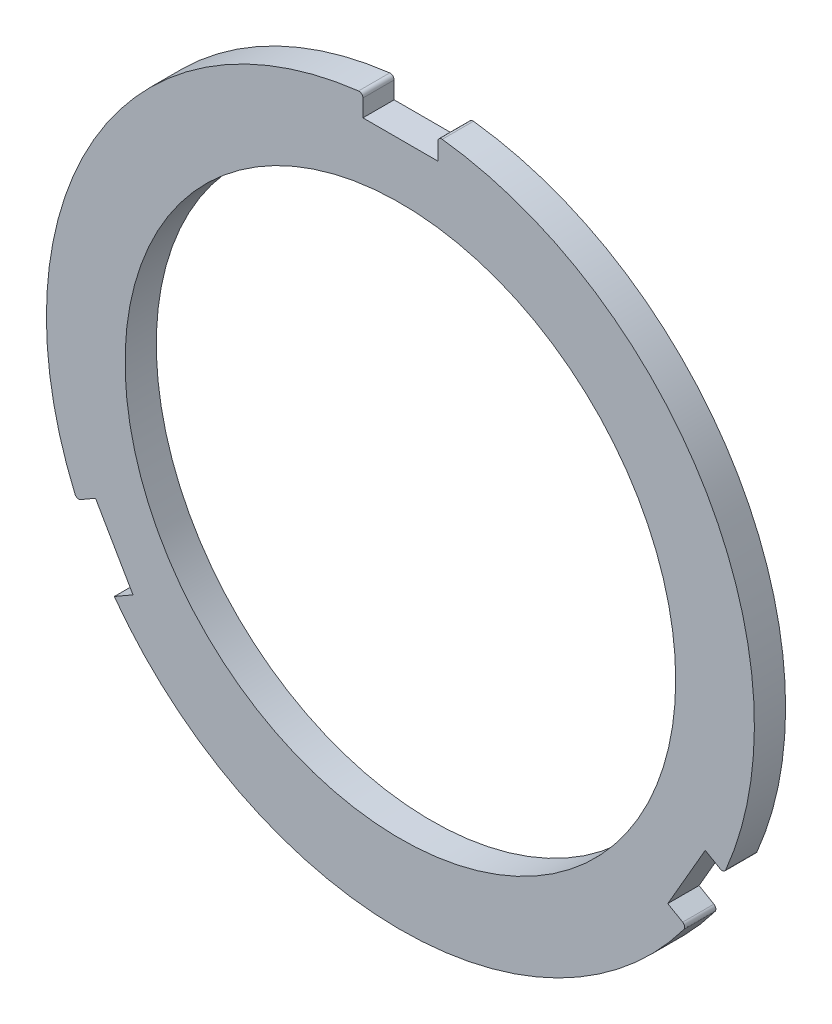
SolidWorks part; units mm, degrees
ref_plane "前基準面" through (0, 0, 0) normal (0, 0, 1) x (1, 0, 0)
ref_plane "上基準面" through (0, 0, 0) normal (0, 1, 0) x (1, 0, 0)
ref_plane "右基準面" through (0, 0, 0) normal (1, 0, 0) x (0, 0, -1)
sketch "Sketch1" plane through (0, 0, 0) normal (0, 0, 1) x (1, 0, 0)
  line L0 (0, 0) -> (0, 33.8653) construction
  line L1 (0, 0) -> (29.3282, -16.9326) construction
  line L2 (0, 0) -> (-29.3282, -16.9326) construction
  line L3 (0, 21) -> (2.3813, 21)
  line L4 (2.3813, 21) -> (2.3813, 22.3736)
  line L5 (20.5668, -9.1246) -> (19.3772, -8.4378)
  line L6 (-2.3812, 22.3736) -> (-2.3813, 21)
  line L7 (-2.3813, 21) -> (0, 21)
  line L8 (19.3772, -8.4378) -> (18.1865, -10.5)
  line L9 (18.1865, -10.5) -> (16.9959, -12.5622)
  line L10 (16.9959, -12.5622) -> (18.1855, -13.249)
  line L11 (-18.1855, -13.249) -> (-16.9959, -12.5622)
  line L12 (-16.9959, -12.5622) -> (-18.1865, -10.5)
  line L13 (-18.1865, -10.5) -> (-19.3772, -8.4378)
  line L14 (-19.3772, -8.4378) -> (-20.5668, -9.1246)
  arc A0 (-2.3812, 22.3736) -> (-20.5668, -9.1246) centre (0, 0) ccw
  circle A1 centre (0, 0) radius 21 construction
  circle A2 centre (0, 0) radius 22.5 construction
  arc A3 (20.5668, -9.1246) -> (2.3813, 22.3736) centre (0, 0) ccw
  arc A4 (-18.1855, -13.249) -> (18.1855, -13.249) centre (0, 0) ccw
  circle A8 centre (0, 0) radius 19 construction
  circle A9 centre (0, 0) radius 17.5
  dimension "D1" = 3.5
  dimension "D3" = 1.5
  dimension "D5" = 45
  dimension "D2" = 1.5
  dimension "D6" = 2.3813
  dimension "D7" = 2.3813
  dimension "D4" = 3
  dimension "D8" = 3
extrude "Boss-Extrude1" add sketch "Sketch1" along normal blind 1.9844
fillet "Fillet1" radius 0.25 6 edges at (-17.5907, -12.9056, 0) (-20.5668, -9.1246, 0.9922) (20.5668, -9.1246, 0.9922) (18.1855, -13.249, 0.9922) (2.3813, 22.3736, 0.9922) (-2.3812, 22.3736, 0.9922)
